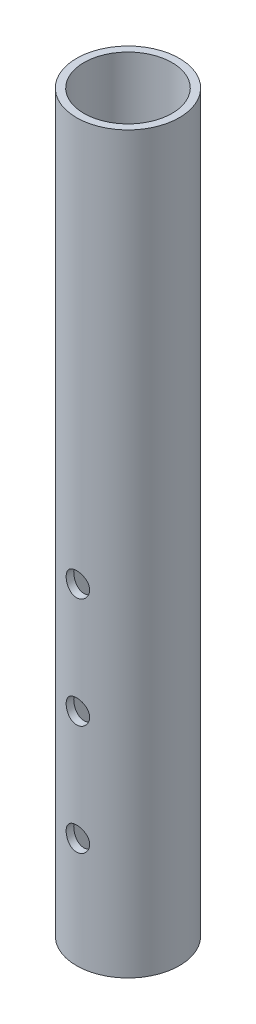
SolidWorks part; units mm, degrees
ref_plane "前视基准面" through (0, 0, 0) normal (0, 0, 1) x (1, 0, 0)
ref_plane "上视基准面" through (0, 0, 0) normal (0, 1, 0) x (1, 0, 0)
ref_plane "右视基准面" through (0, 0, 0) normal (1, 0, 0) x (0, 0, -1)
sketch "草图1" plane through (0, 0, 0) normal (0, 1, 0) x (1, 0, 0)
  circle A0 centre (0, 0) radius 6
  circle A1 centre (0, 0) radius 7
  dimension "D1" = 14
  dimension "D2" = 12
extrude "凸台-拉伸1" add sketch "草图1" along normal blind 100
sketch "草图2" plane through (0, 0, 0) normal (0, 0, 1) x (1, 0, 0)
  line L0 (0, 35.1479) -> (0, 0) construction
  line L1 (-7, 0) -> (7, 0) construction
  line L2 (0, 15) -> (0, 30) construction
  circle A0 centre (0, 15) radius 1.6
  circle A1 centre (0, 30) radius 1.6
  circle A2 centre (0, 45) radius 1.6
  dimension "D1" = 3.2
  dimension "D2" = 15
  dimension "D4" = 15
  dimension "D3" = 3
extrude "切除-拉伸1" cut sketch "草图2" against normal through all both and the other way through all
